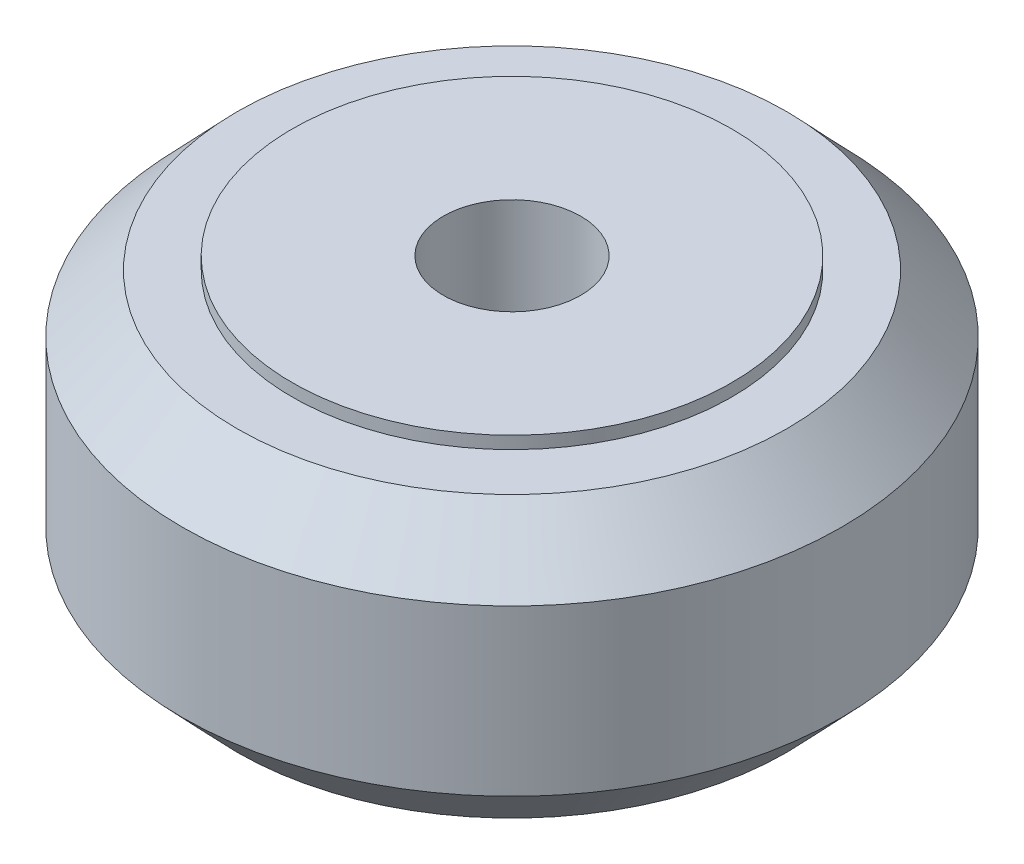
SolidWorks part; units mm, degrees
material "6061 Alloy"
ref_plane "Front Plane" through (0, 0, 0) normal (0, 0, 1) x (1, 0, 0)
ref_plane "Top Plane" through (0, 0, 0) normal (0, 1, 0) x (1, 0, 0)
ref_plane "Right Plane" through (0, 0, 0) normal (1, 0, 0) x (0, 0, -1)
ref_axis "Axis1" through (0, -55, 0) along (0, 1, 0)
sketch "Sketch1" plane through (0, 0, 0) normal (0, 0, 1) x (1, 0, 0)
  line L0 (2.5, -5.555) -> (2.5, 5.555)
  line L1 (2.5, 5.555) -> (8, 5.555)
  line L2 (8, 5.555) -> (8, 5.1)
  line L3 (8, 5.1) -> (10, 5.1)
  line L4 (10, 5.1) -> (12, 3)
  line L5 (0, 0) -> (2.5, 0) construction
  line L6 (10, -5.1) -> (12, -3)
  line L7 (8, -5.1) -> (10, -5.1)
  line L8 (8, -5.555) -> (8, -5.1)
  line L9 (2.5, -5.555) -> (8, -5.555)
  line L10 (12, 3) -> (12, -3)
  line L11 (0, -55) -> (0, 55) construction
  point P2 (2.5, 0)
  dimension "D1" = 12
  dimension "D2" = 11.11
  dimension "D3" = 10.2
  dimension "D4" = 8
  dimension "D5" = 6
  dimension "D6" = 2
  dimension "D7" = 2.5
revolve "Revolve1" add sketch "Sketch1" angle 360 about axis through (0, -55, 0) along (0, 1, 0)
